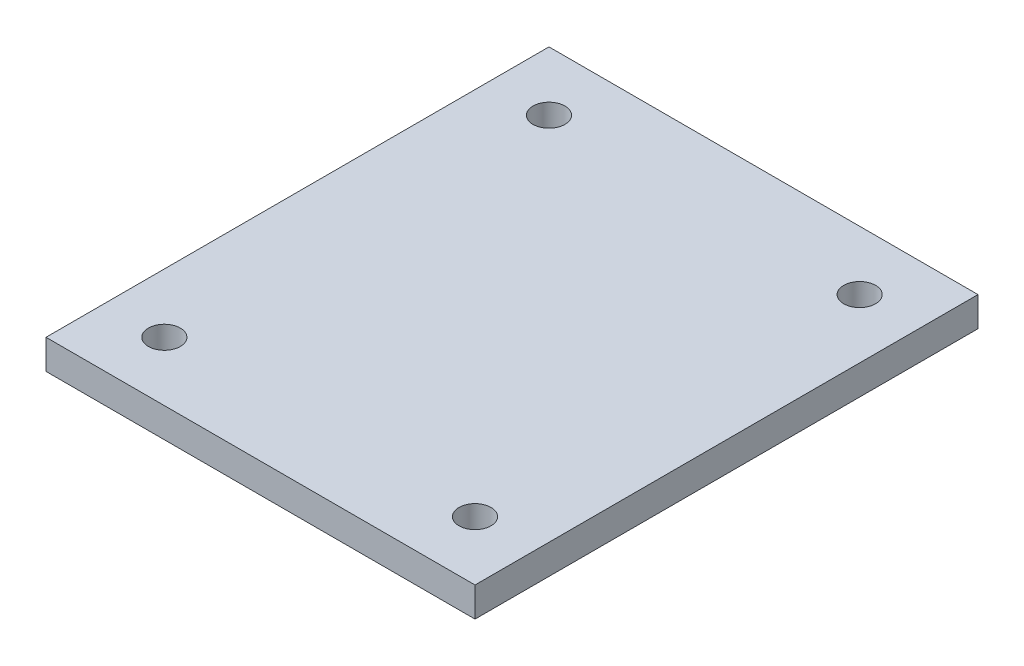
SolidWorks part; units mm, degrees
material "6061 Alloy"
ref_plane "Front Plane" through (0, 0, 0) normal (0, 0, 1) x (1, 0, 0)
ref_plane "Top Plane" through (0, 0, 0) normal (0, 1, 0) x (1, 0, 0)
ref_plane "Right Plane" through (0, 0, 0) normal (1, 0, 0) x (0, 0, -1)
sketch "Sketch1" plane through (0, 0, 0) normal (0, 1, 0) x (1, 0, 0)
  line L1 (-46.0375, 53.975) -> (46.0375, 53.975)
  line L2 (-46.0375, 53.975) -> (-46.0375, -53.975)
  line L3 (-46.0375, -53.975) -> (46.0375, -53.975)
  line L4 (46.0375, 53.975) -> (46.0375, -53.975)
  line L5 (-46.0375, 53.975) -> (46.0375, -53.975) construction
  line L6 (-46.0375, -53.975) -> (46.0375, 53.975) construction
  point P0 (0, 0)
  dimension "D1" = 107.95
  dimension "D2" = 92.075
extrude "Boss-Extrude1" add sketch "Sketch1" along normal blind 6.35
sketch "Sketch3" plane through (0, 0, 0) normal (0, -1, 0) x (1, 0, 0)
  line L0 (0, 0) -> (0, -20.7585) construction
  line L1 (0, 0) -> (-13.1006, 0) construction
  line L2 (-46.0375, -53.975) -> (-46.0375, 53.975) construction
  line L3 (-46.0375, 53.975) -> (46.0375, 53.975) construction
  line L4 (46.0375, -53.975) -> (-46.0375, -53.975) construction
  circle A0 centre (-33.3375, 41.275) radius 3.429
  circle A1 centre (-33.3375, -41.275) radius 3.429
  circle A2 centre (33.3375, 41.275) radius 3.429
  circle A3 centre (33.3375, -41.275) radius 3.429
  dimension "D1" = 12.7
  dimension "D2" = 12.7
  dimension "D3" = 12.7
extrude "Cut-Extrude2" cut sketch "Sketch3" against normal up to next
